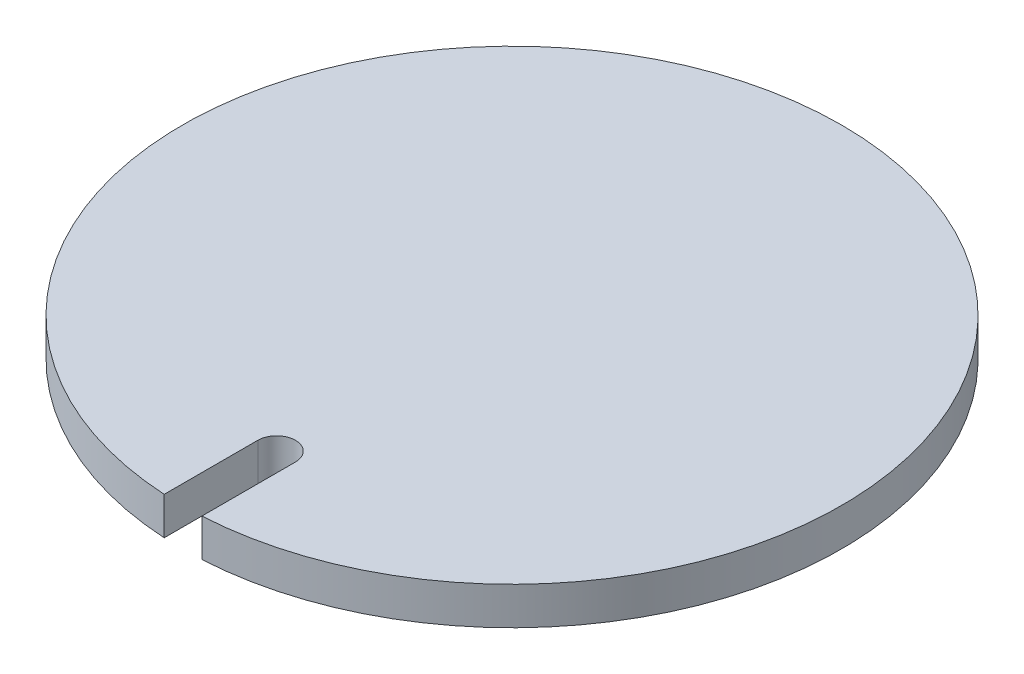
SolidWorks part; units mm, degrees
ref_plane "Front" through (0, 0, 0) normal (0, 0, 1) x (1, 0, 0)
ref_plane "Top" through (0, 0, 0) normal (0, 1, 0) x (1, 0, 0)
ref_plane "Right" through (0, 0, 0) normal (1, 0, 0) x (0, 0, -1)
sketch "Sketch1" plane through (0, 0, 0) normal (0, 1, 0) x (1, 0, 0)
  line L0 (0, -8.75) -> (0, -6.25) construction
  line L1 (-0.5, -8.75) -> (-0.5, -6.25)
  line L2 (0.5, -8.75) -> (0.5, -6.25)
  circle A0 centre (0, 0) radius 8.75
  arc A1 (-0.5, -8.75) -> (0.5, -8.75) centre (0, -8.75) ccw
  arc A2 (0.5, -6.25) -> (-0.5, -6.25) centre (0, -6.25) ccw
  point P5 (0, -7.5)
  dimension "D1" = 17.5
  dimension "D3" = 0.5
  dimension "D2" = 2.5
extrude "Boss-Extrude1" add sketch "Sketch1" along normal blind 1 contours A2 L2 A0 L1
